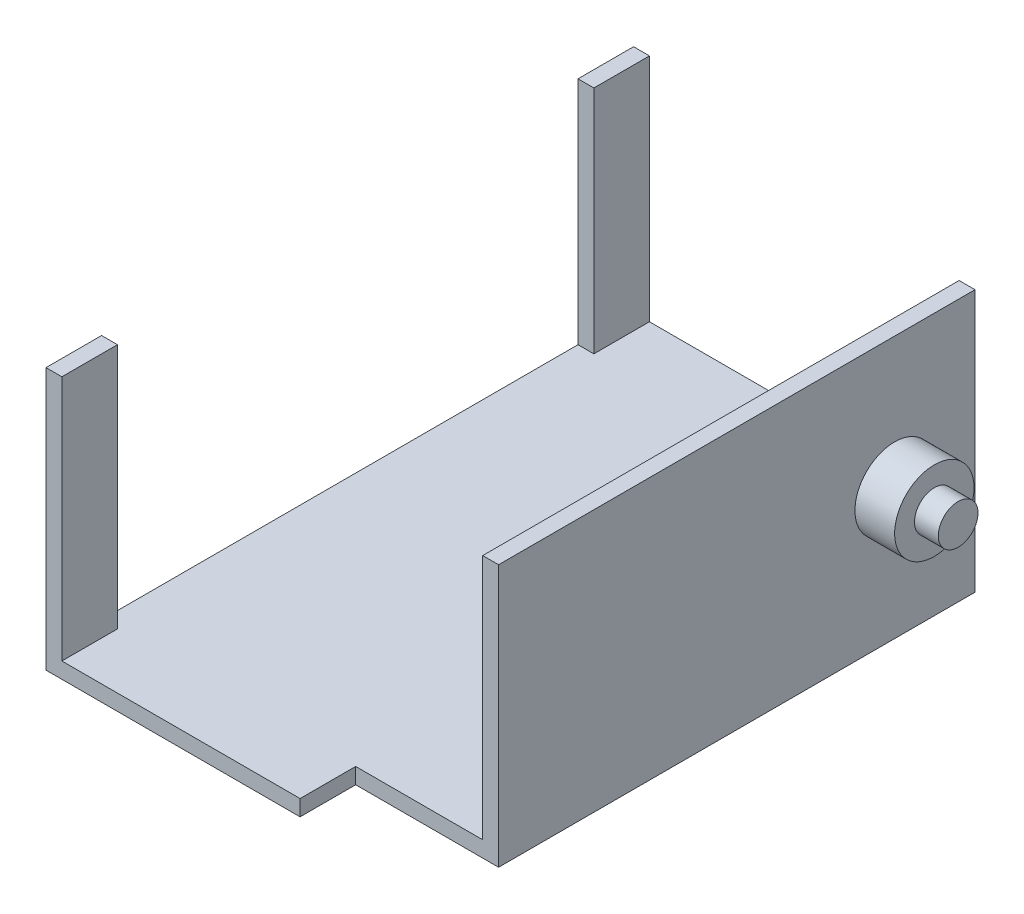
SolidWorks part; units mm, degrees
material "Plastique personnalisé"
ref_plane "Plan de face" through (0, 0, 0) normal (0, 0, 1) x (1, 0, 0)
ref_plane "Plan de dessus" through (0, 0, 0) normal (0, 1, 0) x (1, 0, 0)
ref_plane "Plan de droite" through (0, 0, 0) normal (1, 0, 0) x (0, 0, -1)
sketch "Esquisse1" plane through (0, 0, 0) normal (0, 1, 0) x (1, 0, 0)
  line L1 (8.3882, 24.2506) -> (26.3882, 24.2506)
  line L2 (-23.6118, 24.2506) -> (-23.6118, -35.7494)
  line L3 (8.3882, -35.7494) -> (26.3882, -35.7494)
  line L4 (26.3882, 24.2506) -> (26.3882, -35.7494)
  line L6 (-23.6118, -35.7494) -> (-23.6118, -42.7494)
  line L7 (-23.6118, -42.7494) -> (8.3882, -42.7494)
  line L8 (8.3882, -35.7494) -> (8.3882, -42.7494)
  line L10 (-23.6118, 24.2506) -> (-23.6118, 31.2506)
  line L11 (-23.6118, 31.2506) -> (8.3882, 31.2506)
  line L12 (8.3882, 24.2506) -> (8.3882, 31.2506)
  dimension "D1" = 60
  dimension "D2" = 50
  dimension "D3" = 18
  dimension "D4" = 18
  dimension "D5" = 7
  dimension "D6" = 7
extrude "Boss.-Extru.1" add sketch "Esquisse1" along normal blind 2 contours L11 L12 L1 L4 L3 L8 L7 L6 L2 L10
ref_plane "Plan2" through (0, 0, 42.7494) normal (0, 0, 1) x (1, 0, 0)
sketch "Esquisse4" plane through (0, 0, 42.7494) normal (0, 0, 1) x (1, 0, 0)
  line L0 (-23.6118, 2) -> (-23.6118, 0) construction
  line L1 (-23.6118, 0) -> (-21.6118, 0)
  line L2 (-23.6118, 0) -> (-23.6118, 33)
  line L3 (-23.6118, 33) -> (-21.6118, 33)
  line L4 (-21.6118, 0) -> (-21.6118, 33)
  dimension "D1" = 33
  dimension "D2" = 2
extrude "Boss.-Extru.2" add sketch "Esquisse4" against normal blind 7
ref_plane "Plan3" through (26.3882, 0, 0) normal (1, 0, 0) x (0, 0, -1)
sketch "Esquisse6" plane through (26.3882, 0, 0) normal (1, 0, 0) x (0, 0, -1)
  line L0 (-35.7494, 2) -> (-35.7494, 0) construction
  line L1 (-35.7494, 0) -> (24.2506, 0)
  line L2 (-35.7494, 0) -> (-35.7494, 33)
  line L3 (-35.7494, 33) -> (24.2506, 33)
  line L4 (24.2506, 0) -> (24.2506, 33)
  line L5 (24.2506, 2) -> (24.2506, 0) construction
  dimension "D1" = 0
  dimension "D2" = 33
extrude "Boss.-Extru.3" add sketch "Esquisse6" against normal blind 2
ref_plane "Plan5" through (0, 0, -31.2506) normal (0, 0, -1) x (-1, 0, 0)
sketch "Esquisse7" plane through (0, 0, -31.2506) normal (0, 0, -1) x (-1, 0, 0)
  line L1 (23.6118, 0) -> (21.6118, 0)
  line L2 (23.6118, 0) -> (23.6118, 31)
  line L3 (23.6118, 31) -> (21.6118, 31)
  line L4 (21.6118, 0) -> (21.6118, 31)
  dimension "D1" = 2
  dimension "D2" = 31
extrude "Boss.-Extru.4" add sketch "Esquisse7" against normal blind 7 contours L2 L3 L4 L1
sketch "Esquisse8" plane through (26.3882, 0, 0) normal (1, 0, 0) x (0, 0, -1)
  circle A0 centre (14.1277, 16.4628) radius 5
  dimension "D1" = 10
extrude "Boss.-Extru.5" add sketch "Esquisse8" along normal blind 5
ref_plane "Plan6" through (31.3882, 0, 0) normal (1, 0, 0) x (0, 0, -1)
sketch "Esquisse9" plane through (31.3882, 0, 0) normal (1, 0, 0) x (0, 0, -1)
  circle A0 centre (14.1277, 16.4628) radius 2.5
  circle A1 centre (14.1277, 16.4628) radius 5 construction
  dimension "D1" = 0
extrude "Boss.-Extru.6" add sketch "Esquisse9" along normal blind 3 contours A0
